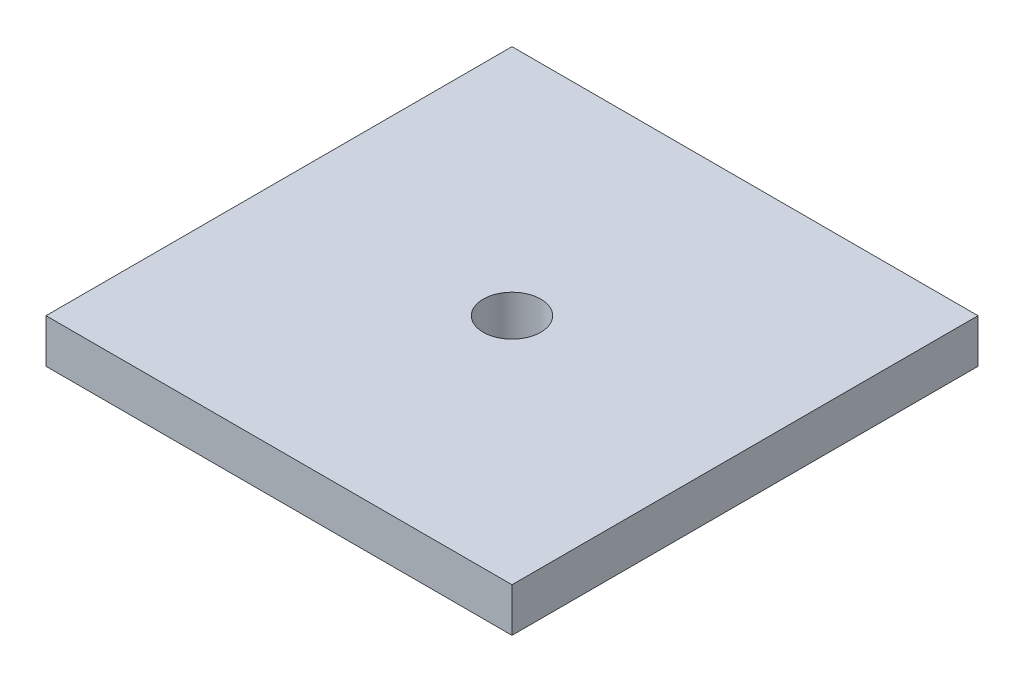
SolidWorks part; units mm, degrees
ref_plane "前视基准面" through (0, 0, 0) normal (0, 0, 1) x (1, 0, 0)
ref_plane "上视基准面" through (0, 0, 0) normal (0, 1, 0) x (1, 0, 0)
ref_plane "右视基准面" through (0, 0, 0) normal (1, 0, 0) x (0, 0, -1)
sketch "草图7" plane through (0, 0, 0) normal (0, 1, 0) x (1, 0, 0)
  line L1 (8.5, -8.5) -> (-8.5, -8.5)
  line L2 (8.5, -8.5) -> (8.5, 8.5)
  line L3 (8.5, 8.5) -> (-8.5, 8.5)
  line L4 (-8.5, -8.5) -> (-8.5, 8.5)
  line L5 (8.5, -8.5) -> (-8.5, 8.5) construction
  line L6 (8.5, 8.5) -> (-8.5, -8.5) construction
  point P0 (0, 0)
  dimension "D1" = 17
  dimension "D2" = 17
extrude "凸台-拉伸5" add sketch "草图7" against normal blind 1.6
sketch "草图8" plane through (0, 0, -8.5) normal (0, 0, -1) x (-1, 0, 0)
  line L0 (-1.5, 1.5) -> (-1.5, 0)
  line L1 (-1.5, 1.5) -> (1.5, 1.5)
  line L2 (-1.5, 0) -> (1.5, 0)
  line L3 (1.5, 1.5) -> (1.5, 0)
  line L4 (0, 0) -> (0, 1.5) construction
  line L5 (-1.5, 0.75) -> (1.5, 0.75) construction
  line L6 (-8.5, 0) -> (8.5, 0) construction
  line L8 (1.25, 0.25) -> (-1.25, 0.25)
  line L9 (1.25, 0.25) -> (1.25, 1.25)
  line L10 (1.25, 1.25) -> (-1.25, 1.25)
  line L11 (-1.25, 0.25) -> (-1.25, 1.25)
  line L12 (1.25, 0.25) -> (-1.25, 1.25) construction
  line L13 (1.25, 1.25) -> (-1.25, 0.25) construction
  point P0 (0, 0.75)
  point P1 (0, 0.75)
sketch "草图11" plane through (0, 0, -8.5) normal (0, 0, -1) x (-1, 0, 0)
  line L4 (-1.25, 0.25) -> (1.25, 0.25)
  line L5 (-1.25, 1.25) -> (-1.25, 0.25)
  line L6 (1.25, 1.25) -> (-1.25, 1.25)
  line L7 (1.25, 0.25) -> (1.25, 1.25)
  line L8 (-1.25, 0.25) -> (1.25, 0.25)
  line L9 (-1.25, 1.25) -> (-1.25, 0.25)
  line L10 (1.25, 1.25) -> (-1.25, 1.25)
  line L11 (1.25, 0.25) -> (1.25, 1.25)
  line L12 (1.5, 1.5) -> (-1.5, 1.5)
  line L13 (-1.5, 1.5) -> (-1.5, 0)
  line L14 (-1.5, 0) -> (1.5, 0)
  line L15 (1.5, 0) -> (1.5, 1.5)
  line L16 (1.5, 1.5) -> (-1.5, 1.5)
  line L17 (-1.5, 1.5) -> (-1.5, 0)
  line L18 (-1.5, 0) -> (1.5, 0)
  line L19 (1.5, 0) -> (1.5, 1.5)
  dimension "D1" = 0
  dimension "D2" = 0
sketch "草图12" plane through (0, 0, 0) normal (0, 1, 0) x (1, 0, 0)
  circle A0 centre (0, 0) radius 1.05
extrude "切除-拉伸3" cut sketch "草图12" against normal through all
